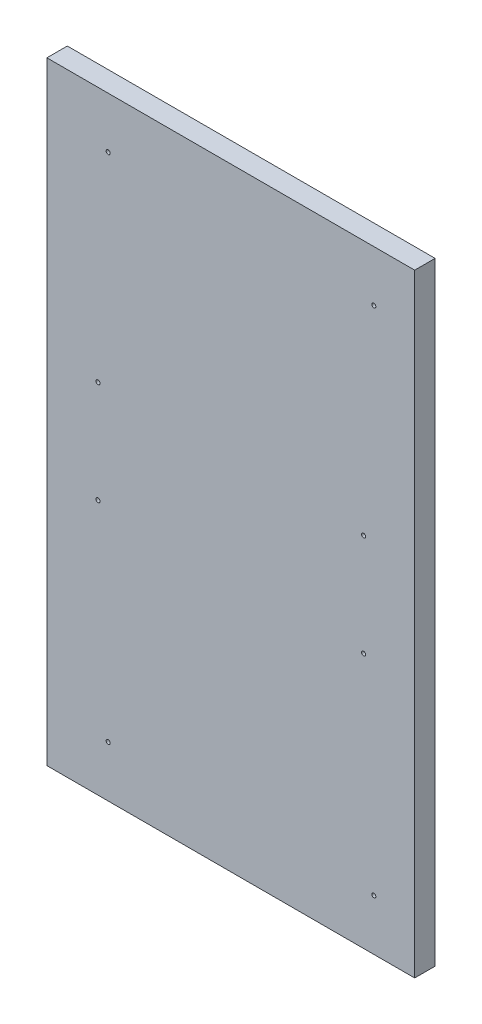
SolidWorks part; units mm, degrees
material "檜木"
ref_plane "前基準面" through (0, 0, 0) normal (0, 0, 1) x (1, 0, 0)
ref_plane "上基準面" through (0, 0, 0) normal (0, 1, 0) x (1, 0, 0)
ref_plane "右基準面" through (0, 0, 0) normal (1, 0, 0) x (0, 0, -1)
sketch "草圖1" plane through (0, 0, 0) normal (0, 0, 1) x (1, 0, 0)
  line L1 (-90, 150) -> (90, 150)
  line L2 (-90, 150) -> (-90, -150)
  line L3 (-90, -150) -> (90, -150)
  line L4 (90, 150) -> (90, -150)
  line L5 (-90, 150) -> (90, -150) construction
  line L6 (-90, -150) -> (90, 150) construction
  point P0 (0, 0)
  dimension "D1" = 180
  dimension "D2" = 300
extrude "填料-伸長1" add sketch "草圖1" along normal blind 10
sketch "草圖2" plane through (0, 0, 0) normal (0, 0, -1) x (-1, 0, 0)
  line L4 (-90, 150) -> (-90, -150)
  line L5 (-90, -150) -> (90, -150)
  line L6 (90, -150) -> (90, 150)
  line L7 (90, 150) -> (-90, 150)
  line L8 (-90, 150) -> (-90, -150)
  line L9 (-90, -150) -> (90, -150)
  line L10 (90, -150) -> (90, 150)
  line L11 (90, 150) -> (-90, 150)
  point P2 (-50, -110)
  point P4 (50, -110)
  point P6 (50, 110)
  point P7 (-50, 110)
  point P8 (0, 0)
  point P9 (0, 0)
  point P10 (0, 0)
  point P11 (0, 0)
  point P12 (0, 0)
  dimension "D2" = 40
  dimension "D3" = 40
  dimension "D4" = 40
  dimension "D5" = 40
  dimension "D1" = 0
hole_wizard "Ø2.0mm 定位孔1" positions "3D草圖1" profile "草圖3" hole size "Ø2.0" standard "Ansi Metric"
sketch3d "3D草圖1"
  point P0 (50, -110, 0)
  point P4 (50, 110, 0)
  point P7 (-50, 110, 0)
  point P10 (-50, -110, 0)
sketch "草圖3" plane through (50, -110, 0) normal (1, 0, 0) x (0, 1, 0)
  line L0 (0, 0) -> (0, 7)
  line L1 (0, 7) -> (1, 6.3991)
  line L2 (1, 6.3991) -> (1, 0)
  line L5 (1, 0) -> (0, 0)
  line L10 (0, 7) -> (-1, 6.3991) construction
  line L11 (0, -6.35) -> (0, 107.95) construction
  dimension "鑽孔直徑" = 2
  dimension "鑽孔深度" = 7
  dimension "導頭角度" = 118
sketch "草圖4" plane through (0, 0, 10) normal (0, 0, 1) x (1, 0, 0)
  line L4 (90, -150) -> (90, 150)
  line L5 (90, 150) -> (-90, 150)
  line L6 (-90, 150) -> (-90, -150)
  line L7 (-90, -150) -> (90, -150)
  line L8 (90, -150) -> (90, 150)
  line L9 (90, 150) -> (-90, 150)
  line L10 (-90, 150) -> (-90, -150)
  line L11 (-90, -150) -> (90, -150)
  point P2 (-60, 125)
  point P4 (-60, -125)
  point P6 (70, 125)
  point P7 (70, -125)
  point P8 (0, 0)
  point P9 (0, 0)
  point P10 (0, 0)
  point P11 (0, 0)
  dimension "D2" = 20
  dimension "D3" = 25
  dimension "D4" = 25
  dimension "D5" = 30
  dimension "D1" = 0
hole_wizard "Ø2.0mm 定位孔2" positions "3D草圖2" profile "草圖5" hole size "Ø2.0" standard "Ansi Metric"
sketch3d "3D草圖2"
  point P0 (-60, 125, 10)
  point P3 (70, 125, 10)
  point P6 (70, -125, 10)
  point P9 (-60, -125, 10)
sketch "草圖5" plane through (-60, 125, 10) normal (1, 0, 0) x (0, -1, 0)
  line L0 (0, 0) -> (0, 7)
  line L1 (0, 7) -> (1, 6.3991)
  line L2 (1, 6.3991) -> (1, 0)
  line L5 (1, 0) -> (0, 0)
  line L10 (0, 7) -> (-1, 6.3991) construction
  line L11 (0, -6.35) -> (0, 107.95) construction
  dimension "鑽孔直徑" = 2
  dimension "鑽孔深度" = 7
  dimension "導頭角度" = 118
sketch "草圖6" plane through (0, 0, 10) normal (0, 0, 1) x (1, 0, 0)
  line L4 (90, -150) -> (90, 150)
  line L5 (90, 150) -> (-90, 150)
  line L6 (-90, 150) -> (-90, -150)
  line L7 (-90, -150) -> (90, -150)
  line L8 (90, -150) -> (90, 150)
  line L9 (90, 150) -> (-90, 150)
  line L10 (-90, 150) -> (-90, -150)
  line L11 (-90, -150) -> (90, -150)
  point P2 (65, 25)
  point P4 (65, -25)
  point P6 (-65, -25)
  point P7 (-65, 25)
  point P8 (0, 0)
  point P9 (0, 0)
  point P10 (0, 0)
  point P11 (0, 0)
  dimension "D2" = 25
  dimension "D3" = 125
  dimension "D4" = 175
  dimension "D5" = 25
  dimension "D1" = 0
hole_wizard "Ø2.0mm 定位孔3" positions "3D草圖3" profile "草圖7" hole size "Ø2.0" standard "Ansi Metric"
sketch3d "3D草圖3"
  point P0 (-65, 25, 10)
  point P3 (65, 25, 10)
  point P6 (65, -25, 10)
  point P9 (-65, -25, 10)
sketch "草圖7" plane through (-65, 25, 10) normal (1, 0, 0) x (0, -1, 0)
  line L0 (0, 0) -> (0, 7)
  line L1 (0, 7) -> (1, 6.3991)
  line L2 (1, 6.3991) -> (1, 0)
  line L5 (1, 0) -> (0, 0)
  line L10 (0, 7) -> (-1, 6.3991) construction
  line L11 (0, -6.35) -> (0, 107.95) construction
  dimension "鑽孔直徑" = 2
  dimension "鑽孔深度" = 7
  dimension "導頭角度" = 118
sketch "草圖8" plane through (0, 0, 0) normal (0, 0, -1) x (-1, 0, 0)
  line L4 (-90, 150) -> (-90, -150)
  line L5 (-90, -150) -> (90, -150)
  line L6 (90, -150) -> (90, 150)
  line L7 (90, 150) -> (-90, 150)
  line L8 (-90, 150) -> (-90, -150)
  line L9 (-90, -150) -> (90, -150)
  line L10 (90, -150) -> (90, 150)
  line L11 (90, 150) -> (-90, 150)
  point P2 (0, 140)
  point P4 (0, 122.8)
  point P6 (0, -122.8)
  point P7 (0, -140)
  point P8 (0, 0)
  point P10 (0, 0)
  point P11 (0, 0)
  dimension "D2" = 10
  dimension "D3" = 17.2
  dimension "D4" = 10
  dimension "D5" = 17.2
  dimension "D1" = 0
hole_wizard "Ø2.0mm 定位孔4" positions "3D草圖4" profile "草圖9" hole size "Ø2.0" standard "Ansi Metric"
sketch3d "3D草圖4"
  point P0 (0, 140, 0)
  point P3 (0, 122.8, 0)
  point P6 (0, -122.8, 0)
  point P9 (0, -140, 0)
sketch "草圖9" plane through (0, 140, 0) normal (1, 0, 0) x (0, 1, 0)
  line L0 (0, 0) -> (0, 7)
  line L1 (0, 7) -> (1, 6.3991)
  line L2 (1, 6.3991) -> (1, 0)
  line L5 (1, 0) -> (0, 0)
  line L10 (0, 7) -> (-1, 6.3991) construction
  line L11 (0, -6.35) -> (0, 107.95) construction
  dimension "鑽孔直徑" = 2
  dimension "鑽孔深度" = 7
  dimension "導頭角度" = 118
